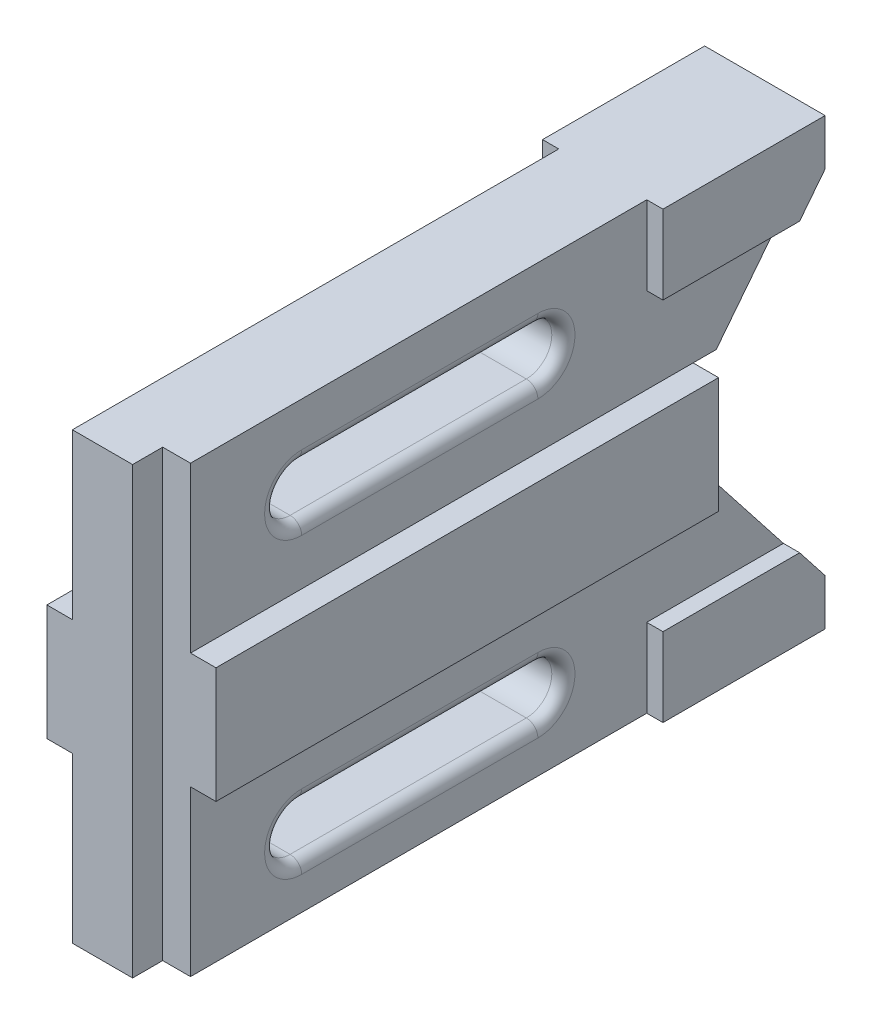
SolidWorks part; units mm, degrees
material "1060 Alloy"
ref_plane "Front Plane" through (0, 0, 0) normal (0, 0, 1) x (1, 0, 0)
ref_plane "Top Plane" through (0, 0, 0) normal (0, 1, 0) x (1, 0, 0)
ref_plane "Right Plane" through (0, 0, 0) normal (1, 0, 0) x (0, 0, -1)
sketch "Sketch1" plane through (0, 0, 0) normal (0, 0, 1) x (1, 0, 0)
  line L1 (-15, 12.5) -> (15, 12.5)
  line L2 (-15, 12.5) -> (-15, -12.5)
  line L3 (-15, -12.5) -> (15, -12.5)
  line L4 (15, 12.5) -> (15, -12.5)
  line L5 (-15, 12.5) -> (15, -12.5) construction
  line L6 (-15, -12.5) -> (15, 12.5) construction
  point P0 (0, 0)
  dimension "D1" = 30
  dimension "D2" = 25
extrude "Boss-Extrude1" add sketch "Sketch1" along normal blind 115
sketch "Sketch3" plane through (0, 0, 0) normal (1, 0, 0) x (0, 0, -1)
  line L0 (-115, 12.5) -> (-115, 48)
  line L1 (-115, 48) -> (25, 48)
  line L2 (25, 48) -> (25, 38)
  line L3 (25, 38) -> (5, 12.5)
  line L4 (5, 12.5) -> (0, 12.5)
  line L5 (-115, -12.5) -> (-115, -48)
  line L6 (-115, -48) -> (25, -48)
  line L7 (25, -48) -> (25, -48.3613)
  line L8 (25, -48.3613) -> (24.82, -48)
  line L9 (5, -12.5) -> (0, -12.5)
  line L10 (25, -48) -> (25, -38)
  line L11 (25, -38) -> (5, -12.5)
  line L12 (0, 12.5) -> (-115, 12.5)
  line L13 (0, -12.5) -> (-115, -12.5)
  dimension "D1" = 140
  dimension "D2" = 35.5
  dimension "D3" = 10
  dimension "D4" = 5
extrude "Boss-Extrude2" add sketch "Sketch3" along normal mid plane 19 contours L9 L13 L5 L6 L10 L11 | L1 L2 L3 L4 L12 L0
sketch "Sketch4" plane through (0, 48, 0) normal (0, 1, 0) x (1, 0, 0)
  line L1 (15, -115) -> (3.5, -115)
  line L2 (15, -115) -> (15, -108.5)
  line L3 (15, -108.5) -> (3.5, -108.5)
  line L4 (3.5, -115) -> (3.5, -108.5)
  dimension "D1" = 6.5
  dimension "D2" = 11.5
extrude "Cut-Extrude1" cut sketch "Sketch4" against normal through all
sketch "Sketch6" plane through (0, 0, 0) normal (1, 0, 0) x (0, 0, -1)
  line L0 (-10, 48) -> (25, 48)
  line L1 (-108.5, 48) -> (25, 48) construction
  line L2 (-10, 48) -> (-10, 31)
  line L3 (-10, 31) -> (19.5098, 31)
  line L4 (25, 38) -> (5, 12.5) construction
  line L5 (19.5098, 31) -> (25, 38)
  line L6 (25, 38) -> (25, 48)
  line L7 (25, -48) -> (-10, -48)
  line L8 (-108.5, -48) -> (25, -48) construction
  line L9 (-10, -48) -> (-10, -31)
  line L10 (-10, -31) -> (19.5098, -31)
  line L11 (25, -38) -> (5, -12.5) construction
  line L12 (19.5098, -31) -> (25, -38)
  line L13 (25, -38) -> (25, -48)
  dimension "D1" = 35
  dimension "D2" = 17
extrude "Boss-Extrude3" add sketch "Sketch6" along normal mid plane 26
sketch "Sketch7" plane through (9.5, 0, 0) normal (1, 0, 0) x (0, 0, -1)
  line L0 (-84.5, 30.5) -> (-33.5, 30.5) construction
  line L1 (-84.5, 36) -> (-33.5, 36)
  line L2 (-84.5, 25) -> (-33.5, 25)
  line L3 (-84.5, -32.8842) -> (-33.5, -32.8842) construction
  line L4 (-84.5, -27.3842) -> (-33.5, -27.3842)
  line L5 (-84.5, -38.3842) -> (-33.5, -38.3842)
  line L6 (-108.5, 48) -> (-10, 48) construction
  line L7 (-115, -48) -> (-115, 48) construction
  arc A0 (-84.5, 36) -> (-84.5, 25) centre (-84.5, 30.5) ccw
  arc A1 (-33.5, 25) -> (-33.5, 36) centre (-33.5, 30.5) ccw
  arc A2 (-84.5, -27.3842) -> (-84.5, -38.3842) centre (-84.5, -32.8842) ccw
  arc A3 (-33.5, -38.3842) -> (-33.5, -27.3842) centre (-33.5, -32.8842) ccw
  point P2 (-59, 30.5)
  point P9 (-59, -32.8842)
  dimension "D2" = 5.5
  dimension "D5" = 30.5
  dimension "D1" = 17.5
  dimension "D3" = 51
  dimension "D4" = 30.5
  dimension "D6" = 51
  dimension "D7" = 63.3842
extrude "Cut-Extrude2" cut sketch "Sketch7" against normal through all
fillet "Fillet1" radius 2.5 4 edges at (9.5, 30.5, 28) (9.5, 25, 59) (9.5, 30.5, 90) (9.5, 36, 59)
fillet "Fillet2" radius 2.5 12 edges at (-9.5, -27.3842, 59) (-9.5, -32.8842, 28) (-9.5, -38.3842, 59) (-9.5, 30.5, 28) (-9.5, 36, 59) (-9.5, 30.5, 90) (9.5, -32.8842, 90) (9.5, -27.3842, 59) (9.5, -32.8842, 28) (-9.5, -32.8842, 90) (-9.5, 25, 59) (9.5, -38.3842, 59)
equation "\"D2@Sketch1\"=96-71"
equation "\"D1@Boss-Extrude1\"=140-25"
equation "\"D2@Sketch3\"=17.75*2"
